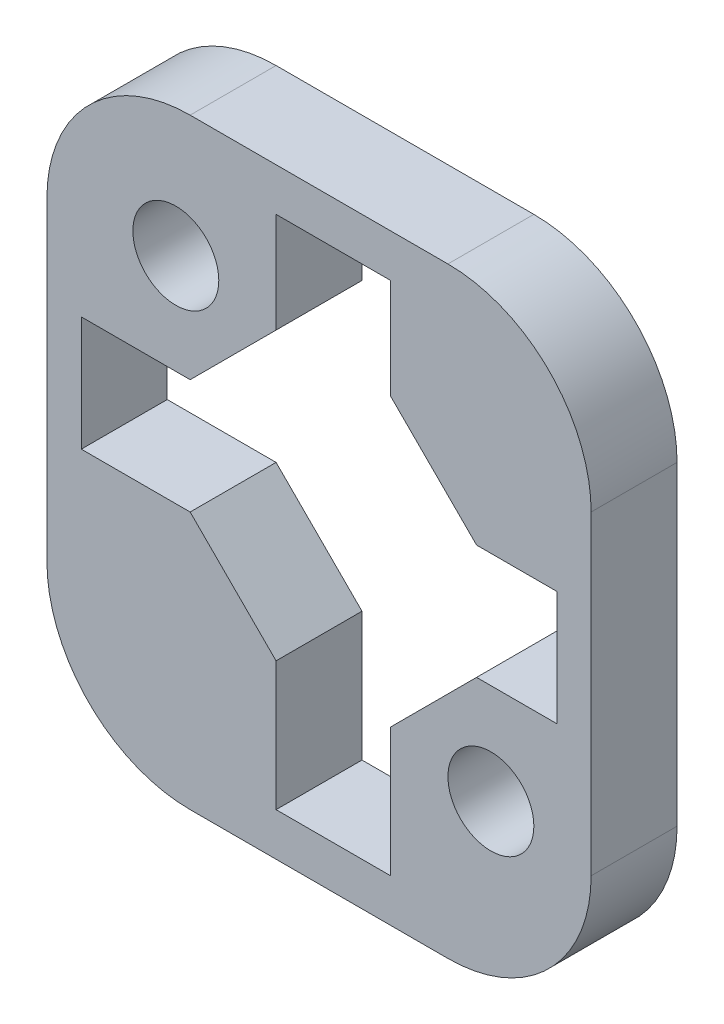
SolidWorks part; units mm, degrees
ref_plane "Plano frontal" through (0, 0, 0) normal (0, 0, 1) x (1, 0, 0)
ref_plane "Plano superior" through (0, 0, 0) normal (0, 1, 0) x (1, 0, 0)
ref_plane "Plano direito" through (0, 0, 0) normal (1, 0, 0) x (0, 0, -1)
sketch "Esboço1" plane through (0, 0, 0) normal (0, 0, 1) x (1, 0, 0)
  line L0 (-8.108, -8.9615) -> (-9.5, -10.5) construction
  line L1 (4.5, 10.5) -> (-4.5, 10.5)
  line L2 (9.5, 5.5) -> (9.5, -5.5)
  line L3 (4.5, -10.5) -> (-4.5, -10.5)
  line L4 (-9.5, 5.5) -> (-9.5, -5.5)
  line L5 (9.5, 10.5) -> (8.108, 8.9615) construction
  line L6 (9.5, -10.5) -> (8.108, -8.9615) construction
  line L7 (-8.108, 8.9615) -> (-9.5, 10.5) construction
  arc A0 (9.5, -5.5) -> (4.5, -10.5) centre (4.5, -5.5) cw
  arc A1 (-4.5, -10.5) -> (-9.5, -5.5) centre (-4.5, -5.5) cw
  arc A2 (-4.5, 10.5) -> (-9.5, 5.5) centre (-4.5, 5.5) ccw
  arc A3 (4.5, 10.5) -> (9.5, 5.5) centre (4.5, 5.5) cw
  point P0 (0, 0)
  dimension "D3" = 5
  dimension "D4" = 5
  dimension "D5" = 5
  dimension "D6" = 5
  dimension "D1" = 19
  dimension "D2" = 21
extrude "Ressalto-extrusão1" add sketch "Esboço1" along normal blind 3
sketch "Esboço2" plane through (0, 0, 0) normal (0, 0, -1) x (-1, 0, 0)
  line L0 (-2.5, -1.5) -> (-2.5, -9)
  line L1 (9, 2.5) -> (1.5, 2.5)
  line L2 (9, 2.5) -> (9, -1.5)
  line L3 (9, -1.5) -> (1.5, -1.5)
  line L4 (-9, 2.5) -> (-9, -1.5)
  line L5 (-9.5, -5.5) -> (-9.5, 5.5) construction
  line L6 (-4.5, 10.5) -> (4.5, 10.5) construction
  line L7 (1.5, 9) -> (-2.5, 9)
  line L8 (1.5, 9) -> (1.5, 2.5)
  line L9 (1.5, -9) -> (-2.5, -9)
  line L10 (-2.5, 9) -> (-2.5, 2.5)
  line L12 (0.6311, -2) -> (0, 0) construction
  line L13 (-2.5, -1.5) -> (-9, -1.5)
  line L14 (-2.5, 2.5) -> (-9, 2.5)
  line L15 (1.5, -1.5) -> (1.5, -9)
  point P0 (0, 0)
  point P6 (0, 0)
  dimension "D1" = 4
  dimension "D2" = 4
  dimension "D3" = 18
  dimension "D4" = 18
  dimension "D5" = 6.5
  dimension "D6" = 6.5
  dimension "D7" = 0.5
  dimension "D8" = 1.5
extrude "Corte-extrusão1" cut sketch "Esboço2" against normal blind 3
sketch "Esboço3" plane through (0, 0, 3) normal (0, 0, 1) x (1, 0, 0)
  line L0 (9, -1.5) -> (2.5, -1.5) construction
  line L1 (2.5, -1.5) -> (2.5, -9) construction
  line L2 (-1.5, 2.5) -> (-1.5, 9) construction
  line L3 (-9, 2.5) -> (-1.5, 2.5) construction
  circle A0 centre (6, -5) radius 1.5
  circle A1 centre (-5, 6) radius 1.5
  dimension "D1" = 3
  dimension "D2" = 3
  dimension "D4" = 3.5
  dimension "D5" = 3.5
  dimension "D6" = 3.5
  dimension "D3" = 3.5
extrude "Corte-extrusão2" cut sketch "Esboço3" against normal blind 3
chamfer "Chanfro1" distance 3 angle 45 4 edges at (2.5, -1.5, 1.5) (2.5, 2.5, 1.5) (-1.5, 2.5, 1.5) (-1.5, -1.5, 1.5)
sketch "Esboço4" plane through (-9, 0, 0) normal (1, 0, 0) x (0, 0, -1)
  line L4 (0, -1.5) -> (0, 2.5)
  line L5 (0, 2.5) -> (-3, 2.5)
  line L6 (-3, 2.5) -> (-3, -1.5)
  line L7 (-3, -1.5) -> (0, -1.5)
  line L8 (0, -1.5) -> (0, 2.5)
  line L9 (0, 2.5) -> (-3, 2.5)
  line L10 (-3, 2.5) -> (-3, -1.5)
  line L11 (-3, -1.5) -> (0, -1.5)
  dimension "D1" = 0
extrude "Ressalto-extrusão2" add sketch "Esboço4" along normal blind 0.7
sketch "Esboço5" plane through (9, 0, 0) normal (-1, 0, 0) x (0, 0, 1)
  line L4 (0, 2.5) -> (0, -1.5)
  line L5 (0, -1.5) -> (3, -1.5)
  line L6 (3, -1.5) -> (3, 2.5)
  line L7 (3, 2.5) -> (0, 2.5)
  line L8 (0, 2.5) -> (0, -1.5)
  line L9 (0, -1.5) -> (3, -1.5)
  line L10 (3, -1.5) -> (3, 2.5)
  line L11 (3, 2.5) -> (0, 2.5)
  dimension "D1" = 0
extrude "Ressalto-extrusão3" add sketch "Esboço5" along normal blind 0.7
